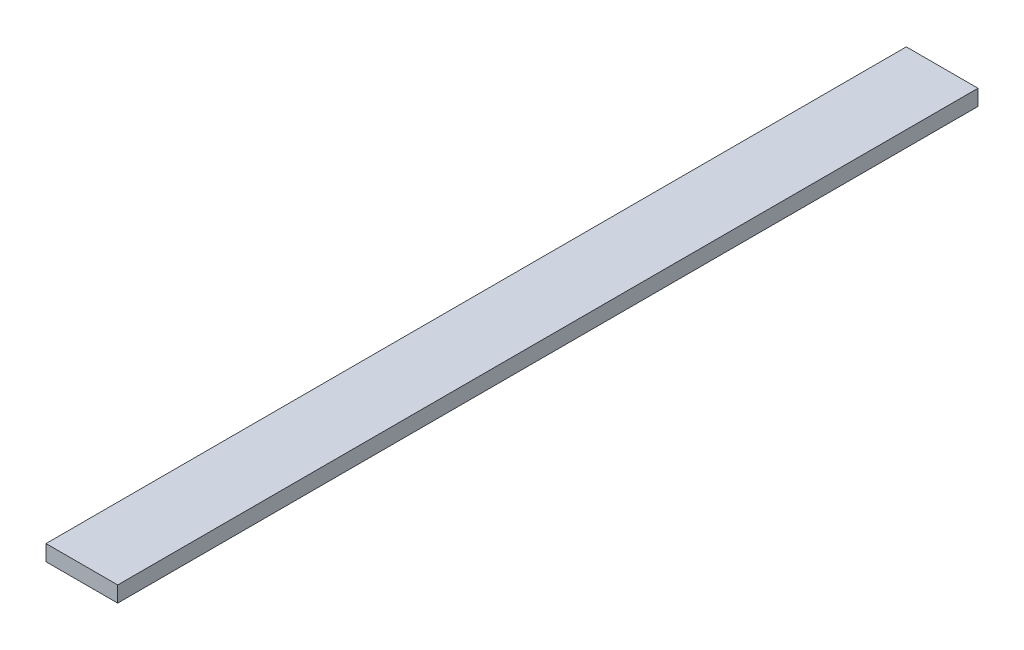
SolidWorks part; units mm, degrees
material "Pine"
ref_plane "Ön Düzlem" through (0, 0, 0) normal (0, 0, 1) x (1, 0, 0)
ref_plane "Üst Düzlem" through (0, 0, 0) normal (0, 1, 0) x (1, 0, 0)
ref_plane "Sağ Düzlem" through (0, 0, 0) normal (1, 0, 0) x (0, 0, -1)
sketch "Çizim1" plane through (0, 0, 0) normal (0, 1, 0) x (1, 0, 0)
  line L1 (-50, -600) -> (50, -600)
  line L2 (-50, -600) -> (-50, 600)
  line L3 (-50, 600) -> (50, 600)
  line L4 (50, -600) -> (50, 600)
  line L5 (-50, -600) -> (50, 600) construction
  line L6 (-50, 600) -> (50, -600) construction
  point P0 (0, 0)
  dimension "D1" = 1200
  dimension "D2" = 100
extrude "Yükseklik-Ekstrüzyon1" add sketch "Çizim1" along normal blind 22
